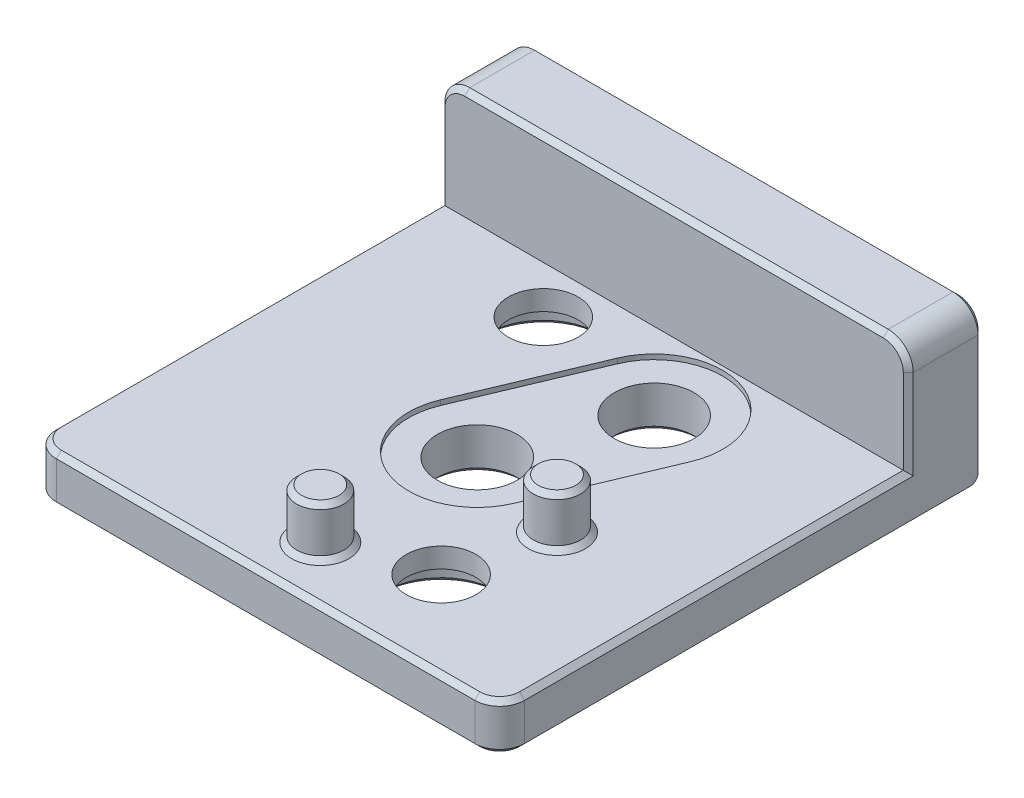
SolidWorks part; units mm, degrees
ref_plane "Front Plane" through (0, 0, 0) normal (0, 0, 1) x (1, 0, 0)
ref_plane "Top Plane" through (0, 0, 0) normal (0, 1, 0) x (1, 0, 0)
ref_plane "Right Plane" through (0, 0, 0) normal (1, 0, 0) x (0, 0, -1)
sketch "Sketch1" plane through (0, 0, 0) normal (1, 0, 0) x (0, 0, -1)
  line L1 (0, 0) -> (19.4, 0)
  line L2 (0, 0) -> (0, -1.9)
  line L3 (0, -1.9) -> (19.4, -1.9)
  line L4 (19.4, 0) -> (19.4, -1.9)
  line L5 (19.4, 0) -> (16.4, 0)
  line L6 (19.4, 0) -> (19.4, 4.4)
  line L7 (19.4, 4.4) -> (16.4, 4.4)
  line L8 (16.4, 0) -> (16.4, 4.4)
  dimension "D1" = 1.9
  dimension "D2" = 3
  dimension "D3" = 16.4
  dimension "D4" = 6.3
extrude "Boss-Extrude1" add sketch "Sketch1" along normal mid plane 18.8 contours L4 L1 L2 L3 | L8 L1 L6 L7
sketch "Sketch2" plane through (0, 0, 0) normal (0, 1, 0) x (1, 0, 0)
  line L0 (0, 0) -> (0, 8.5)
  line L1 (9.4, 0) -> (-9.4, 0) construction
  line L2 (9.4, 0) -> (9.4, 16.4) construction
  circle A0 centre (0, 8.5) radius 1.6
  circle A1 centre (2.1, 13.5) radius 1.6
  circle A2 centre (3.55, 3.5) radius 1.4
  circle A3 centre (-3.35, 14.5) radius 1.4
  dimension "D2" = 3.2
  dimension "D5" = 2.8
  dimension "D1" = 8.5
  dimension "D3" = 13.5
  dimension "D4" = 7.3
  dimension "D6" = 12.75
  dimension "D7" = 14.5
  dimension "D8" = 5.85
  dimension "D9" = 3.5
extrude "Cut-Extrude1" cut sketch "Sketch2" against normal through all
sketch "Sketch3" plane through (0, 0, 0) normal (0, 1, 0) x (1, 0, 0)
  line L0 (0, 8.5) -> (2.1, 13.5) construction
  line L1 (-2.5355, 9.5649) -> (-0.4355, 14.5649)
  line L2 (2.5355, 7.4351) -> (4.6355, 12.4351)
  arc A0 (-2.5355, 9.5649) -> (2.5355, 7.4351) centre (0, 8.5) ccw
  arc A1 (4.6355, 12.4351) -> (-0.4355, 14.5649) centre (2.1, 13.5) ccw
  circle A2 centre (2.1, 13.5) radius 1.6 construction
  circle A3 centre (0, 8.5) radius 1.6 construction
  point P2 (1.05, 11)
  dimension "D1" = 2.75
extrude "Cut-Extrude2" cut sketch "Sketch3" against normal blind 0.2
sketch "Sketch4" plane through (0, -1.9, 0) normal (0, -1, 0) x (1, 0, 0)
  circle A0 centre (-3.35, -14.5) radius 2.25
  circle A1 centre (3.55, -3.5) radius 2.25
  circle A2 centre (-3.35, -14.5) radius 1.4 construction
  circle A3 centre (3.55, -3.5) radius 1.4 construction
  dimension "D1" = 4.5
extrude "Cut-Extrude3" cut sketch "Sketch4" against normal blind 1.1
fillet "Fillet1" radius 1 4 edges at (-9.4, 4.4, -17.9) (9.4, 4.4, -17.9) (-9.4, -0.95, 0) (9.4, -0.95, 0)
sketch "Sketch5" plane through (0, 0, 0) normal (0, 1, 0) x (1, 0, 0)
  line L0 (9.4, 1) -> (9.4, 16.4) construction
  line L1 (8.4, 0) -> (-8.4, 0) construction
  circle A0 centre (0, 2.2) radius 0.95
  circle A1 centre (4.4, 7.3) radius 0.95
  dimension "D1" = 1.9
  dimension "D2" = 5
  dimension "D3" = 9.4
  dimension "D4" = 2.2
  dimension "D5" = 7.3
extrude "Boss-Extrude2" add sketch "Sketch5" along normal blind 2
fillet "Fillet4" radius 0.5 1 edges at (0, -1.9, -19.4)
chamfer "Chamfer1" distance 0.2 angle 45 30 edges at (9.4, 1.7, -16.4) (9.1071, 4.1071, -16.4) (0, 4.4, -16.4) (-9.4, 1.7, -16.4) (-9.1071, 4.1071, -16.4) (9.4, -1.9, -9.95) (9.4, -1.7536, -19.2536) (9.1071, -1.9, -0.2929) (9.4, 1, -19.4) (0, -1.9, 0) (9.1071, 4.1071, -19.4) (-9.1071, -1.9, -0.2929) (0, 4.4, -19.4) (-9.4, -1.9, -9.95) (-9.1071, 4.1071, -19.4) (-9.4, -1.7536, -19.2536) (-9.4, 1, -19.4) (9.4, 0, -8.7) (9.1071, 0, -0.2929) (0, 0, 0) (-9.1071, 0, -0.2929) (-9.4, 0, -8.7) (0, 0, -1.25) (0, 2, -1.25) (4.4, 0, -6.35) (4.4, 2, -6.35) (0, -1.9, -6.9) (2.1, -1.9, -11.9) (3.55, -1.9, -5.75) (-3.35, -1.9, -16.75)
